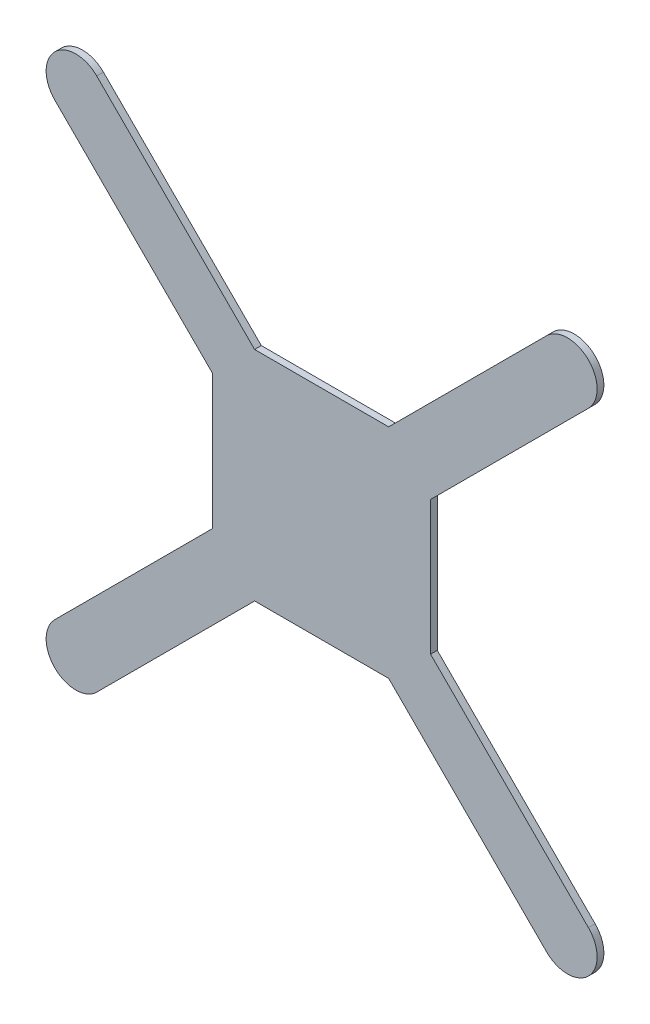
SolidWorks part; units mm, degrees
ref_plane "前视基准面" through (0, 0, 0) normal (0, 0, 1) x (1, 0, 0)
ref_plane "上视基准面" through (0, 0, 0) normal (0, 1, 0) x (1, 0, 0)
ref_plane "右视基准面" through (0, 0, 0) normal (1, 0, 0) x (0, 0, -1)
other "Configuration Table"
sketch "草图1" plane through (0, 0, 0) normal (0, 0, 1) x (1, 0, 0)
  line L0 (0, 0) -> (0, -16.3537) construction
  line L1 (-65, 65) -> (-159.099, 159.099) construction
  line L2 (-40, 65) -> (40, 65)
  line L3 (-65, 40) -> (-65, -40)
  line L4 (-40, -65) -> (40, -65)
  line L5 (65, 40) -> (65, -40)
  line L6 (0, 0) -> (32.5134, 0) construction
  line L7 (40, -65) -> (65, -40)
  line L8 (65, 65) -> (159.099, 159.099) construction
  line L9 (40, 65) -> (65, 40)
  line L10 (-65, 40) -> (-40, 65)
  line L11 (-65, -40) -> (-40, -65)
  line L12 (40, 65) -> (134.2247, 159.2247)
  line L13 (65, 40) -> (159.2247, 134.2247)
  line L14 (65, -40) -> (159.2247, -134.2247)
  line L15 (40, -65) -> (134.2247, -159.2247)
  line L16 (-40, -65) -> (-134.2247, -159.2247)
  line L17 (-65, -40) -> (-159.2247, -134.2247)
  line L18 (-65, 40) -> (-159.2247, 134.2247)
  line L19 (-40, 65) -> (-134.2247, 159.2247)
  arc A0 (134.2247, 159.2247) -> (159.2247, 134.2247) centre (146.7247, 146.7247) cw
  arc A1 (134.2247, -159.2247) -> (159.2247, -134.2247) centre (146.7247, -146.7247) ccw
  arc A2 (-134.2247, -159.2247) -> (-159.2247, -134.2247) centre (-146.7247, -146.7247) cw
  arc A3 (-134.2247, 159.2247) -> (-159.2247, 134.2247) centre (-146.7247, 146.7247) ccw
  point P0 (-65, 65)
  point P1 (65, -65)
  point P3 (-65, -65)
  point P4 (65, 65)
  point P9 (65, 65)
  point P15 (-65, 65)
  dimension "D3" = 45
  dimension "D2" = 45
  dimension "D8" = 130
  dimension "D9" = 415
  dimension "D1" = 45
  dimension "D4" = 45
  dimension "D5" = 45
  dimension "D6" = 25
  dimension "D7" = 25
extrude "凸台-拉伸1" add sketch "草图1" along normal blind 4 contours A2 L16 L11 L17 | L19 A3 L18 L10 | L3 L11 L4 L7 L5 L9 L2 L10 | L15 A1 L14 L7 | A0 L12 L9 L13
